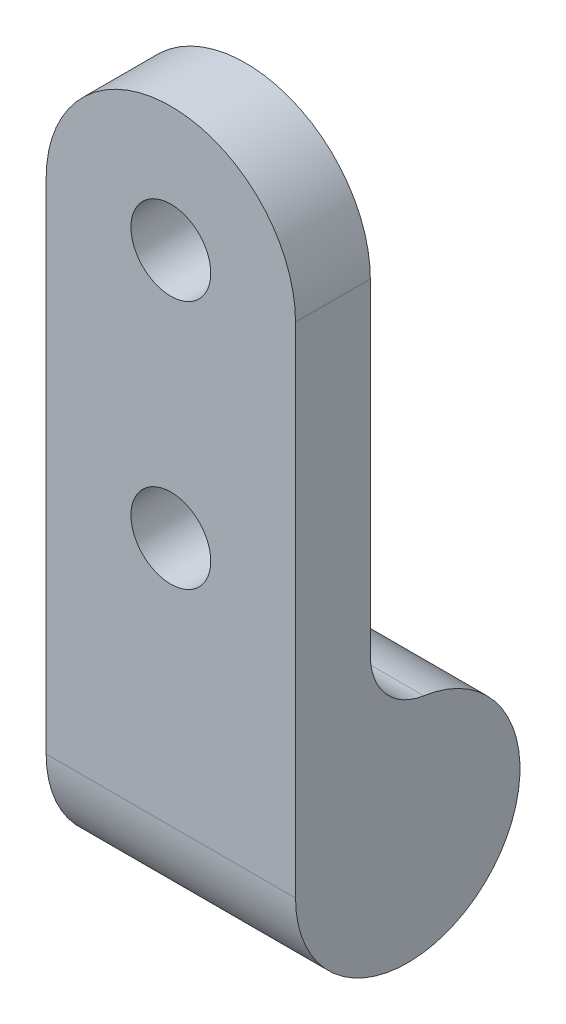
SolidWorks part; units mm, degrees
ref_plane "前视基准面" through (0, 0, 0) normal (0, 0, 1) x (1, 0, 0)
ref_plane "上视基准面" through (0, 0, 0) normal (0, 1, 0) x (1, 0, 0)
ref_plane "右视基准面" through (0, 0, 0) normal (1, 0, 0) x (0, 0, -1)
sketch "草图2" plane through (0, 0, 0) normal (1, 0, 0) x (0, 0, -1)
  line L1 (-4.5, 25) -> (-1.5, 25)
  line L2 (-4.5, 25) -> (-4.5, 0)
  line L4 (-1.5, 25) -> (-1.5, 6.9282)
  arc A0 (-4.5, 0) -> (0.6429, 4.4538) centre (0, 0) ccw
  arc A1 (-1.5, 6.9282) -> (0.6429, 4.4538) centre (1, 6.9282) ccw
  point P7 (-4.5, 0)
  dimension "D1" = 9
  dimension "D4" = 2.5
  dimension "D2" = 25
  dimension "D3" = 3
extrude "凸台-拉伸1" add sketch "草图2" along normal blind 10
sketch "草图3" plane through (0, 0, 1.5) normal (0, 0, -1) x (-1, 0, 0)
  line L0 (-10, 6.9282) -> (-10, 25) construction
  line L1 (0, 6.9282) -> (0, 25) construction
  line L2 (-10, 25) -> (0, 25) construction
  line L3 (-10, 20) -> (-10, 25)
  line L4 (-10, 25) -> (0, 25)
  line L5 (0, 25) -> (0, 20)
  arc A0 (-10, 20) -> (0, 20) centre (-5, 20) cw
  circle A1 centre (-5, 20) radius 1.6
  circle A2 centre (-5, 10) radius 1.6
  point P16 (0, 0)
  point P17 (0, 0)
  point P18 (0, 0)
  line M1 (0, 6.9282) -> (0, 25)
  line M2 (0, 25) -> (-10, 25)
  line M3 (-10, 25) -> (-10, 6.9282)
  dimension "D1" = 3.2
  dimension "D2" = 3.2
  dimension "D3" = 10
extrude "切除-拉伸1" cut sketch "草图3" against normal through all contours A0 L4 M3 | A0 M2 M1 | A1 | A2
